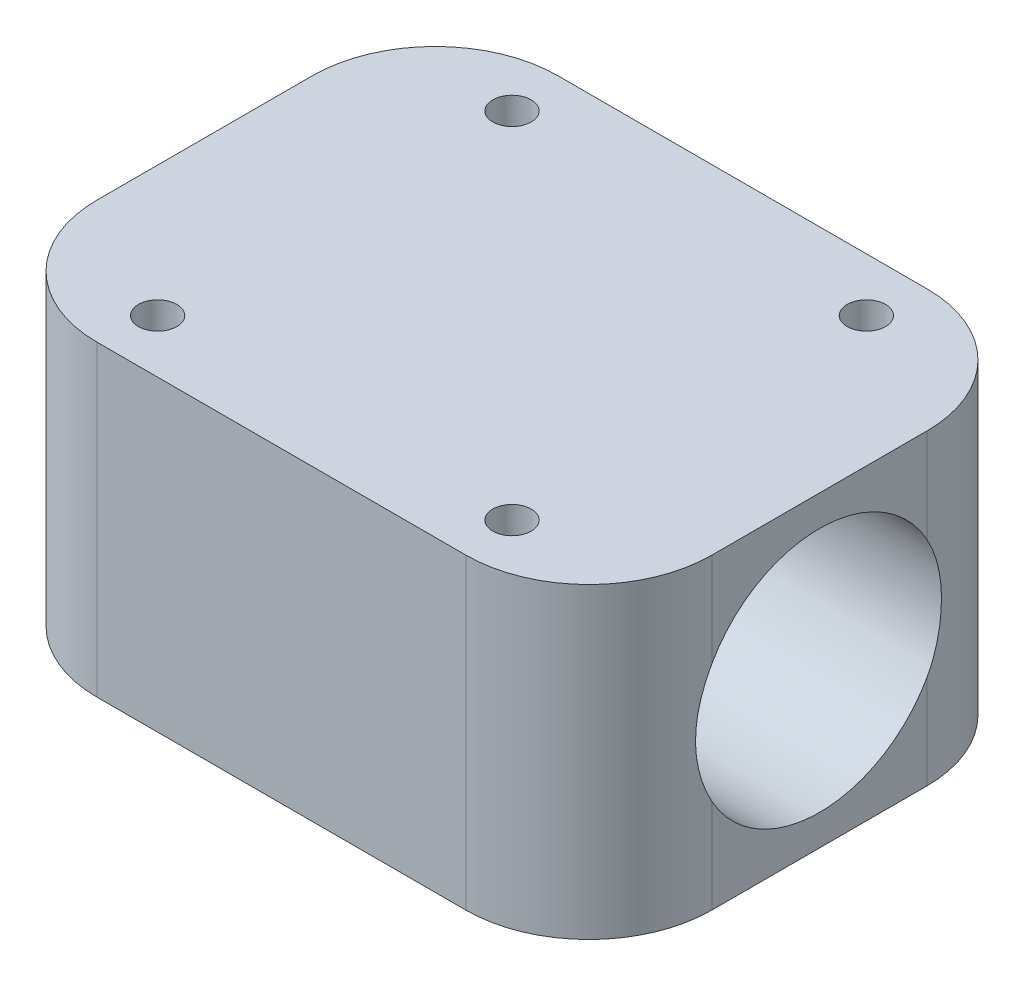
SolidWorks part; units mm, degrees
ref_plane "前基準面" through (0, 0, 0) normal (0, 0, 1) x (1, 0, 0)
ref_plane "上基準面" through (0, 0, 0) normal (0, 1, 0) x (1, 0, 0)
ref_plane "右基準面" through (0, 0, 0) normal (1, 0, 0) x (0, 0, -1)
sketch "草圖2" plane through (0, 0, 0) normal (0, 1, 0) x (1, 0, 0)
  line L1 (-12, 15) -> (12, 15)
  line L2 (-20, 7) -> (-20, -7)
  line L3 (-12, -15) -> (12, -15)
  line L4 (20, 7) -> (20, -7)
  line L5 (-20, 15) -> (20, -15) construction
  line L6 (-20, -15) -> (20, 15) construction
  line L7 (-11.5258, 11.5258) -> (11.5258, 11.5258) construction
  line L8 (-11.5258, 11.5258) -> (-11.5258, -11.5258) construction
  line L9 (-11.5258, -11.5258) -> (11.5258, -11.5258) construction
  line L10 (11.5258, 11.5258) -> (11.5258, -11.5258) construction
  line L11 (-11.5258, 11.5258) -> (11.5258, -11.5258) construction
  line L12 (-11.5258, -11.5258) -> (11.5258, 11.5258) construction
  circle A0 centre (-11.5258, 11.5258) radius 1.25
  circle A1 centre (11.5258, 11.5258) radius 1.25
  circle A2 centre (11.5258, -11.5258) radius 1.25
  circle A3 centre (-11.5258, -11.5258) radius 1.25
  arc A4 (12, 15) -> (20, 7) centre (12, 7) cw
  arc A5 (12, -15) -> (20, -7) centre (12, -7) ccw
  arc A6 (-20, -7) -> (-12, -15) centre (-12, -7) ccw
  arc A7 (-12, 15) -> (-20, 7) centre (-12, 7) ccw
  point P0 (0, 0)
  point P6 (0, 0)
  dimension "D1" = 2.5
  dimension "D5" = 8
  dimension "D2" = 32.6
  dimension "D3" = 30
  dimension "D4" = 40
extrude "填料-伸長1" add sketch "草圖2" along normal blind 20
sketch "草圖3" plane through (20, 0, 0) normal (1, 0, 0) x (0, 0, -1)
  line L0 (7, 20) -> (-7, 0) construction
  circle A0 centre (0, 10) radius 8
  point P6 (-15, 0)
  point P7 (0, 0)
  point P8 (7, 20)
  point P10 (-7, 0)
  dimension "D1" = 16
extrude "除料-伸長1" cut sketch "草圖3" against normal through all
